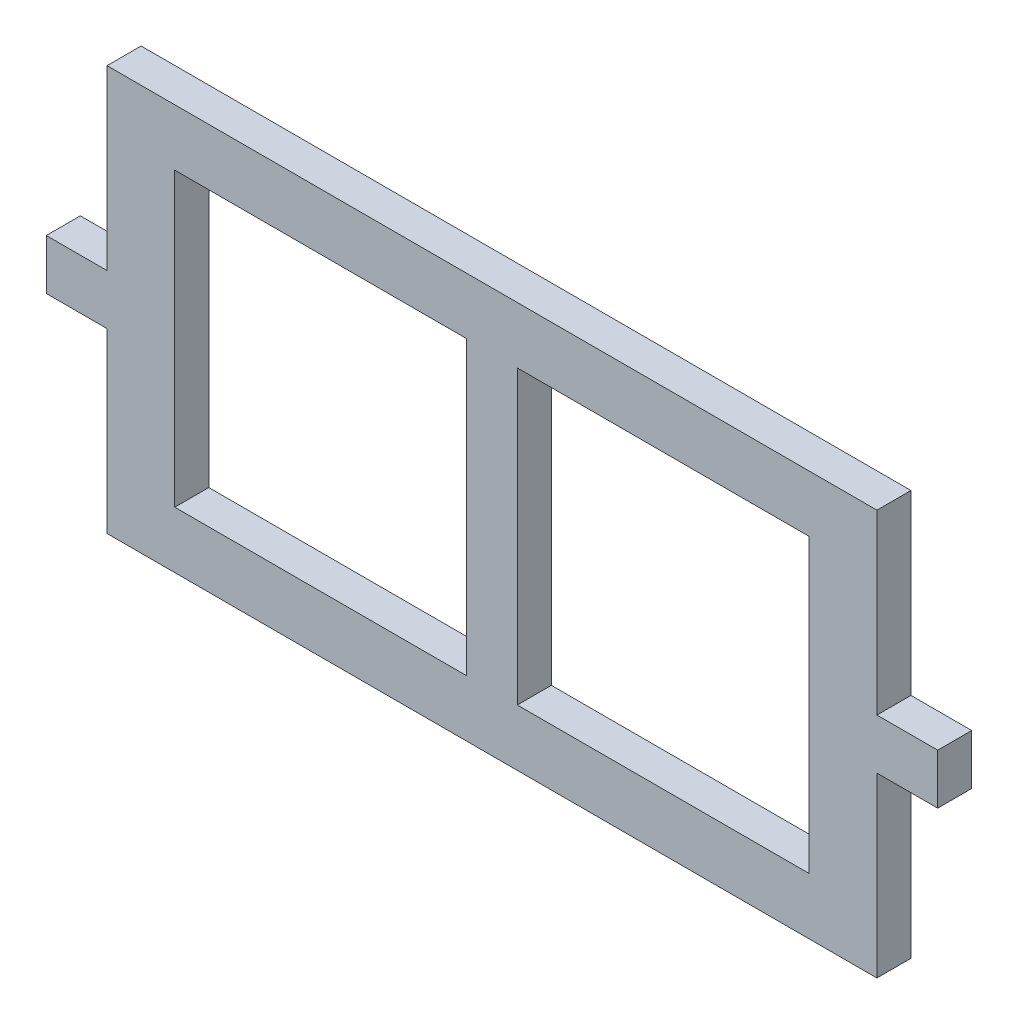
SolidWorks part; units mm, degrees
material "Acrylic (Medium-high impact)"
ref_plane "Front" through (0, 0, 0) normal (0, 0, 1) x (1, 0, 0)
ref_plane "Top" through (0, 0, 0) normal (0, 1, 0) x (1, 0, 0)
ref_plane "Right" through (0, 0, 0) normal (1, 0, 0) x (0, 0, -1)
sketch "Sketch1" plane through (0, 0, 0) normal (0, 0, 1) x (1, 0, 0)
  line L1 (-120.65, -63.5) -> (120.65, -63.5)
  line L2 (-120.65, -63.5) -> (-120.65, 63.5)
  line L3 (-120.65, 63.5) -> (120.65, 63.5)
  line L4 (120.65, -63.5) -> (120.65, 63.5)
  line L5 (-120.65, -63.5) -> (120.65, 63.5) construction
  line L6 (-120.65, 63.5) -> (120.65, -63.5) construction
  point P0 (0, 0)
  dimension "D1" = 241.3
  dimension "D2" = 127
extrude "Boss-Extrude1" add sketch "Sketch1" along normal blind 10.668
sketch "Sketch3" plane through (0, 0, 10.668) normal (0, 0, 1) x (1, 0, 0)
  line L0 (-120.65, 63.5) -> (-120.65, -63.5) construction
  line L1 (-99.4375, 45.75) -> (-7.9375, 45.75)
  line L2 (-99.4375, 45.75) -> (-99.4375, -45.75)
  line L3 (-99.4375, -45.75) -> (-7.9375, -45.75)
  line L4 (-7.9375, 45.75) -> (-7.9375, -45.75)
  line L5 (7.9375, 45.75) -> (99.4375, 45.75)
  line L6 (7.9375, 45.75) -> (7.9375, -45.75)
  line L7 (7.9375, -45.75) -> (99.4375, -45.75)
  line L8 (99.4375, 45.75) -> (99.4375, -45.75)
  line L9 (-7.9375, -45.75) -> (7.9375, -45.75)
  line L10 (-120.65, -63.5) -> (120.65, -63.5) construction
  point P11 (-120.65, 0)
  point P12 (-99.4375, 0)
  point P13 (-7.9375, 0)
  point P14 (7.9375, 0)
  point P17 (0, -45.75)
  point P20 (0, -63.5)
  dimension "D1" = 91.5
  dimension "D2" = 15.875
extrude "Cut-Extrude1" cut sketch "Sketch3" against normal through all contours L4 L1 L2 L3 | L8 L5 L6 L7
sketch "Sketch4" plane through (0, 0, 10.668) normal (0, 0, 1) x (1, 0, 0)
  line L0 (-120.65, 7.874) -> (-139.7, 7.874)
  line L1 (-120.65, 63.5) -> (-120.65, -63.5) construction
  line L2 (-139.7, 7.874) -> (-139.7, -7.874)
  line L3 (-139.7, -7.874) -> (-120.65, -7.874)
  line L8 (-120.65, 7.874) -> (-120.65, -7.874)
  line L9 (0, 0) -> (-139.7, 0) construction
  point P12 (-139.7, 0)
  dimension "D1" = 19.05
  dimension "D2" = 15.748
extrude "Boss-Extrude2" add sketch "Sketch4" against normal through all
mirror "Mirror1" about plane through (0, 0, 0) normal (1, 0, 0) of "Boss-Extrude2"
